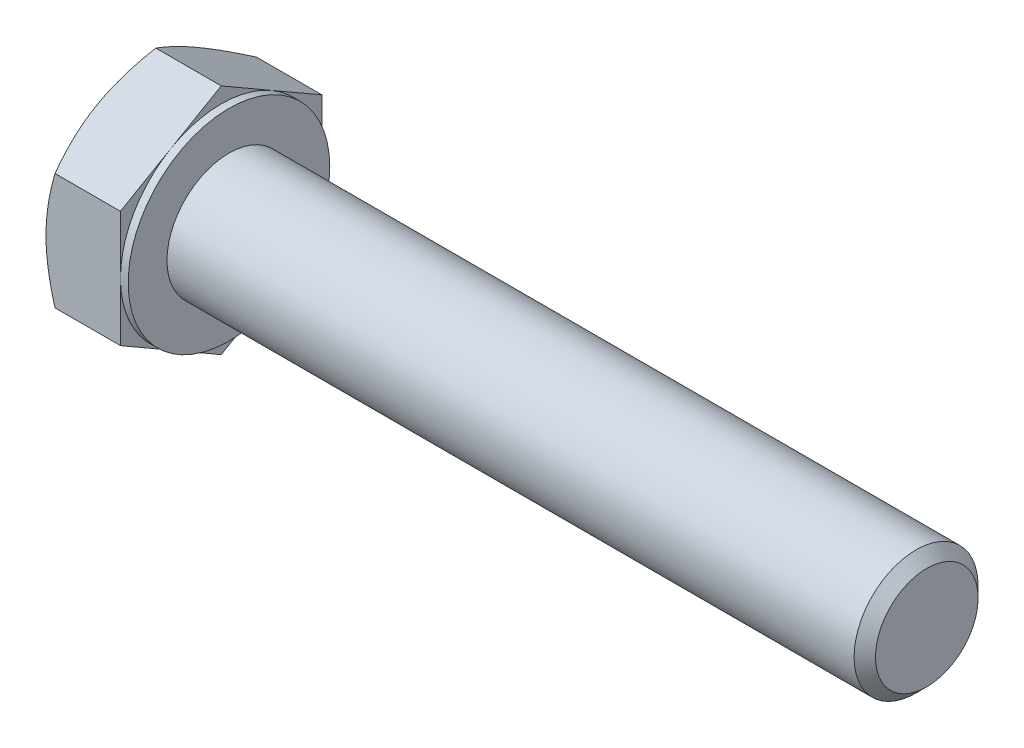
SolidWorks part; units mm, degrees
extrude "BaseHead" add sketch "Sketch1" along normal blind 5.3
sketch "Sketch1" plane through (0, 0, 0) normal (1, 0, 0) x (0, 0, -1)
  line L0 (6.5, 3.7528) -> (6.5, -3.7528)
  line L1 (-6.5, 3.7528) -> (-6.5, -3.7528)
  line L2 (6.5, -3.7528) -> (0, -7.5056)
  line L3 (0, -7.5056) -> (-6.5, -3.7528)
  line L4 (6.5, 3.7528) -> (0, 7.5056)
  line L5 (0, 7.5056) -> (-6.5, 3.7528)
  dimension "Width_flats" = 13
  dimension "D2" = 120
  dimension "D3" = 6.5
  dimension "D4" = 6.5
  dimension "D5" = 6.5
revolve "HeadChamfer" cut sketch "Sketch3" angle 360 about L6
sketch "Sketch3" plane through (0, 0, 0) normal (0, 0, 1) x (1, 0, 0)
  line L0 (0, 6.5) -> (3.4673, 12.5056)
  line L1 (0, 7.5056) -> (0, 3.7528) construction
  line L2 (3.4673, 12.5056) -> (3.4673, 17.5056)
  line L3 (3.4673, 17.5056) -> (-10, 17.5056)
  line L4 (-10, 17.5056) -> (-10, 6.5)
  line L5 (-10, 6.5) -> (0, 6.5)
  line L6 (0, 0) -> (99.06, 0) construction
  line L7 (5.3, 7.5056) -> (0, 7.5056) construction
  dimension "D1" = 6.5
  dimension "D2" = 5
  dimension "D3" = 10
  dimension "D4" = 5
  dimension "Head_ch_ang" = 30
ref_plane "Plane1" through (0, 0, 0) normal (0, 0, 1) x (1, 0, 0)
ref_plane "Plane2" through (0, 0, 0) normal (0, 1, 0) x (1, 0, 0)
ref_plane "Plane3" through (0, 0, 0) normal (1, 0, 0) x (0, 0, -1)
other "Configuration Table"
sketch "BodySke" plane through (0, 0, 0) normal (0, 0, 1) x (1, 0, 0)
  line L0 (0, 3.7528) -> (0, -3.7528) construction
  line L1 (0, 0) -> (50.3, 0)
  line L2 (0, 0) -> (0, 4)
  line L3 (0, 4) -> (49.6095, 4)
  line L4 (50.3, 0) -> (50.3, 3.3095)
  line L5 (5.3, 7.5056) -> (5.3, 3.7528) construction
  line L6 (50.3, 3.3095) -> (49.6095, 4)
  line L7 (0, 0) -> (96.52, 0) construction
  line L8 (50.3, -3.3095) -> (49.6095, -4) construction
  line L9 (0, -4) -> (49.6095, -4) construction
  line L10 (6.55, 15.24) -> (6.55, -1.27) construction
  line L11 (28.3, 15.24) -> (28.3, -1.27) construction
  line L12 (5.3, 3.7528) -> (5.3, -3.7528) construction
  dimension "Diameter" = 8
revolve "BaseBody" add sketch "BodySke" angle 360 about L7
cosmetic thread "ThreadCosmetic" parameters "Thread_length"=29, "Thread_minor"=6.619
sketch "Sketch4" plane through (0, 0, 0) normal (0, 0, 1) x (1, 0, 0)
  line L1 (5.3, 7.5056) -> (5.3, 3.7528) construction
  line L2 (5.3, 6.5) -> (4.8, 6.5)
  line L3 (5.3, 6.5) -> (5.3, 17.5056)
  line L4 (5.3, 17.5056) -> (4.8, 17.5056)
  line L5 (0, 0) -> (95.25, 0) construction
  line L6 (0, 0) -> (96.52, 0) construction
  line L7 (4.8, 6.5) -> (4.8, 17.5056)
  line L8 (5.3, 7.5056) -> (0.5806, 7.5056) construction
  dimension "D2" = 10
  dimension "D1" = 13
revolve "BearingFace" cut sketch "Sketch4" angle 360 about L5
fillet "HeadFillet" [suppressed] radius 0.4
sketch "ThdSchSke" plane through (0, 0, 0) normal (0, 0, 1) x (1, 0, 0)
  line L0 (21.3, -3.3095) -> (20.8165, -4)
  line L1 (21.3, -3.3095) -> (21.7835, -4)
  line L2 (21.7835, -4) -> (21.7835, -5)
  line L3 (-3.175, 0) -> (5.1513, 0) construction
  line L5 (21.7835, -5) -> (20.8165, -5)
  line L6 (20.8165, -5) -> (20.8165, -4)
  dimension "Thread_minor" = 6.619
  dimension "Diameter" = 8
  dimension "Start" = 21.3
revolve "ThreadSchematic" [suppressed] cut sketch "ThdSchSke" angle 360 about L3
pattern_linear "ThdSchPat" [suppressed]
equation "\"D3@Sketch1\" = \"Width_flats@Sketch1\" / 2"
equation "\"D4@Sketch1\" = \"D3@Sketch1\""
equation "\"D5@Sketch1\" = \"D4@Sketch1\""
equation "\"Thread_minor@ThreadCosmetic\"=\"Minor_dia@BodySke\""
equation "\"D1@Sketch3\" = \"Width_flats@Sketch1\" / 2"
equation "\"D1@Sketch4\" = \"Width_flats@Sketch1\""
equation "\"Thread_minor@ThdSchSke\" = \"Minor_dia@BodySke\""
equation "\"Diameter@ThdSchSke\" = \"Diameter@BodySke\""
equation "\"Overcut@ThdSchSke\" = \"Diameter@BodySke\" * 1.25"
equation "\"Start@ThdSchSke\" = \"Head_ht@BaseHead\" + \"Length@BodySke\" - \"Thread_length@ThreadCosmetic\"  '---Non-countersunk---"
equation "\"Num_threads@ThdSchPat\" = int( \"Thread_length@ThreadCosmetic\" / \"Advance@BodySke\" + 0.999 )  + 1"
equation "\"Advance@ThdSchPat\" = \"Thread_length@ThreadCosmetic\" /  (\"Num_threads@ThdSchPat\" - 1) 'relax it"
equation "\"Num_threads@ThdSchPat\" = \"Num_threads@ThdSchPat\" - sgn( \"Num_threads@ThdSchPat\" - 1) '---chamfered tips only---"
